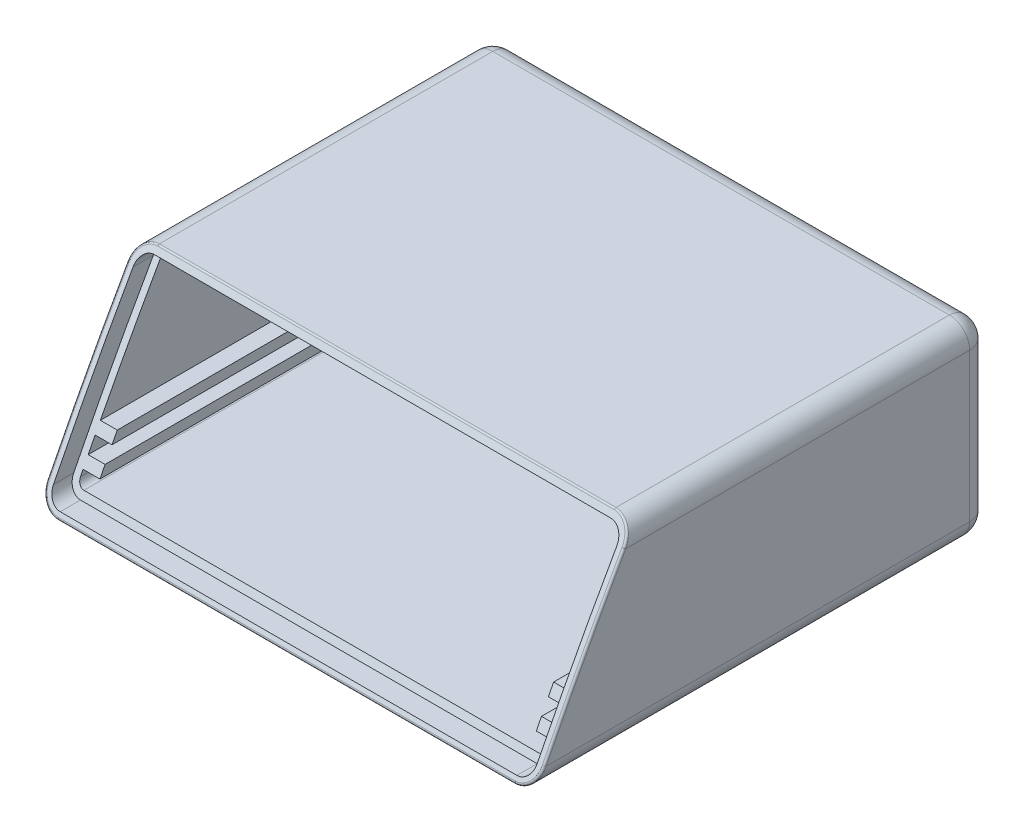
SolidWorks part; units mm, degrees
ref_plane "Front Plane" through (0, 0, 0) normal (0, 0, 1) x (1, 0, 0)
ref_plane "Top Plane" through (0, 0, 0) normal (0, 1, 0) x (1, 0, 0)
ref_plane "Right Plane" through (0, 0, 0) normal (1, 0, 0) x (0, 0, -1)
sketch "Sketch1" plane through (0, 0, 0) normal (0, 1, 0) x (1, 0, 0)
  line L1 (-36.79, -33.75) -> (36.79, -33.75)
  line L2 (-36.79, -33.75) -> (-36.79, 33.75)
  line L3 (-36.79, 33.75) -> (36.79, 33.75)
  line L4 (36.79, -33.75) -> (36.79, 33.75)
  line L5 (-36.79, -33.75) -> (36.79, 33.75) construction
  line L6 (-36.79, 33.75) -> (36.79, -33.75) construction
  point P0 (0, 0)
  dimension "D1" = 67.5
  dimension "D2" = 73.58
extrude "Boss-Extrude1" add sketch "Sketch1" along normal blind 28
fillet "Fillet1" radius 3 4 edges at (36.79, 28, 0) (36.79, 0, 0) (-36.79, 0, 0) (-36.79, 28, 0)
shell "Shell1" thickness 2
sketch "Sketch2" plane through (-36.79, 0, 0) normal (-1, 0, 0) x (0, 0, 1)
  line L0 (-33.75, 28) -> (33.75, 28) construction
  line L1 (18.75, 28) -> (33.75, 28)
  line L2 (33.75, 28) -> (33.75, 0)
  arc A0 (33.75, 0) -> (18.75, 28) centre (-392.2189, -210.1797) ccw
  dimension "D1" = 15
  dimension "D2" = 475
extrude "Cut-Extrude1" cut sketch "Sketch2" against normal through all
sketch "Sketch3" plane through (0, 0, -33.75) normal (0, 0, -1) x (-1, 0, 0)
  line L0 (-7.15, 18.7) -> (7.15, 18.7)
  line L1 (-6.95, 18.5) -> (6.95, 18.5) construction
  line L2 (-6.95, 18.5) -> (-6.95, 2.2) construction
  line L3 (-6.95, 2.2) -> (6.95, 2.2) construction
  line L4 (6.95, 18.5) -> (6.95, 2.2) construction
  line L5 (7.15, 18.7) -> (7.15, 2)
  line L6 (-7.15, 2) -> (7.15, 2)
  line L7 (-7.15, 18.7) -> (-7.15, 2)
  line L8 (27.25, 17.2) -> (38.3, 17.2)
  line L9 (27.45, 17) -> (38.1, 17) construction
  line L10 (27.45, 17) -> (27.45, 3.35) construction
  line L11 (27.45, 3.35) -> (38.1, 3.35) construction
  line L12 (38.1, 17) -> (38.1, 3.35) construction
  line L13 (38.3, 17.2) -> (38.3, 3.15)
  line L14 (27.25, 3.15) -> (38.3, 3.15)
  line L15 (27.25, 17.2) -> (27.25, 3.15)
  dimension "D1" = 0.2
  dimension "D2" = 0.2
fillet "Fillet2" radius 3 8 edges at (35.9113, 27.1213, -33.75) (36.79, 14, -33.75) (35.9113, 0.8787, -33.75) (0, 0, -33.75) (-35.9113, 0.8787, -33.75) (-36.79, 14, -33.75) (-35.9113, 27.1213, -33.75) (0, 28, -33.75)
sketch "Sketch4" plane through (0, 0, -31.75) normal (0, 0, 1) x (1, 0, 0)
  line L0 (33.79, 27) -> (-33.79, 27)
  line L1 (-35.79, 25) -> (-35.79, 3)
  line L2 (-33.79, 1) -> (33.79, 1)
  line L3 (35.79, 3) -> (35.79, 25)
  line L4 (33.79, 26) -> (-33.79, 26)
  line L5 (-34.79, 25) -> (-34.79, 3)
  line L6 (-33.79, 2) -> (33.79, 2)
  line L7 (34.79, 3) -> (34.79, 25)
  line L8 (33.79, 26) -> (-33.79, 26)
  line L9 (-34.79, 25) -> (-34.79, 3)
  line L10 (-33.79, 2) -> (33.79, 2)
  line L11 (34.79, 3) -> (34.79, 25)
  arc A0 (-33.79, 27) -> (-35.79, 25) centre (-33.79, 25) ccw
  arc A1 (-35.79, 3) -> (-33.79, 1) centre (-33.79, 3) ccw
  arc A2 (33.79, 1) -> (35.79, 3) centre (33.79, 3) ccw
  arc A3 (35.79, 25) -> (33.79, 27) centre (33.79, 25) ccw
  arc A4 (-33.79, 26) -> (-34.79, 25) centre (-33.79, 25) ccw
  arc A5 (-34.79, 3) -> (-33.79, 2) centre (-33.79, 3) ccw
  arc A6 (33.79, 2) -> (34.79, 3) centre (33.79, 3) ccw
  arc A7 (34.79, 25) -> (33.79, 26) centre (33.79, 25) ccw
  arc A8 (-33.79, 26) -> (-34.79, 25) centre (-33.79, 25) ccw
  arc A9 (-34.79, 3) -> (-33.79, 2) centre (-33.79, 3) ccw
  arc A10 (33.79, 2) -> (34.79, 3) centre (33.79, 3) ccw
  arc A11 (34.79, 25) -> (33.79, 26) centre (33.79, 25) ccw
  dimension "D1" = 0
  dimension "D2" = 1
extrude "Cut-Extrude3" cut sketch "Sketch4" against normal offset from surface (18.9934 mm away) 3 from offset 80
fillet "Fillet3" radius 0.3 8 edges at (35.773, 27.2511, 19.1831) (36.79, 14.0774, 26.5098) (35.5191, 0.5484, 33.479) (0, 0, 33.75) (-35.9799, 0.9496, 33.2802) (-36.79, 14.0774, 26.5098) (-35.4767, 27.4809, 19.0504) (0, 28, 18.75)
sketch "Sketch5" plane through (0, 0, -31.75) normal (0, 0, 1) x (1, 0, 0)
  line L1 (34.79, 5.25) -> (32.29, 5.25)
  line L2 (34.79, 5.25) -> (34.79, 3.75)
  line L3 (34.79, 3.75) -> (32.29, 3.75)
  line L4 (32.29, 5.25) -> (32.29, 3.75)
  line L5 (34.79, 7.05) -> (40.64, 7.05) construction
  line L6 (34.79, 7.25) -> (32.29, 7.25)
  line L7 (34.79, 7.25) -> (34.79, 8.75)
  line L8 (34.79, 8.75) -> (32.29, 8.75)
  line L9 (32.29, 7.25) -> (32.29, 8.75)
  line L10 (-40.64, 7.05) -> (40.64, 7.05) construction
  line L11 (40.64, 5.45) -> (34.79, 5.45) construction
  line L12 (-40.64, 5.45) -> (40.64, 5.45) construction
  line L14 (-34.79, 8.75) -> (-32.29, 8.75)
  line L15 (-34.79, 8.75) -> (-34.79, 7.25)
  line L16 (-34.79, 7.25) -> (-32.29, 7.25)
  line L17 (-32.29, 8.75) -> (-32.29, 7.25)
  line L18 (-34.79, 25) -> (-34.79, 3) construction
  line L19 (-34.79, 5.25) -> (-32.29, 5.25)
  line L20 (-34.79, 5.25) -> (-34.79, 3.75)
  line L21 (-34.79, 3.75) -> (-32.29, 3.75)
  line L22 (-32.29, 5.25) -> (-32.29, 3.75)
  line L23 (34.79, 25) -> (34.79, 3) construction
  dimension "D1" = 0.2
  dimension "D2" = 0.2
  dimension "D3" = 1.5
  dimension "D4" = 2.5
extrude "Boss-Extrude2" add sketch "Sketch5" along normal up to surface (59.8691 mm away)
sketch "Sketch6" plane through (0, 0, -33.75) normal (0, 0, -1) x (-1, 0, 0)
  line L0 (-7.15, 18.7) -> (7.15, 18.7)
  line L1 (-6.95, 18.5) -> (6.95, 18.5) construction
  line L2 (-6.95, 18.5) -> (-6.95, 2.2) construction
  line L3 (-6.95, 2.2) -> (6.95, 2.2) construction
  line L4 (6.95, 18.5) -> (6.95, 2.2) construction
  line L5 (7.15, 18.7) -> (7.15, 2)
  line L6 (-7.15, 2) -> (7.15, 2)
  line L7 (-7.15, 18.7) -> (-7.15, 2)
  line L8 (20.9, 17.2) -> (31.95, 17.2)
  line L9 (21.1, 17) -> (31.75, 17) construction
  line L10 (21.1, 17) -> (21.1, 3.35) construction
  line L11 (21.1, 3.35) -> (31.75, 3.35) construction
  line L12 (31.75, 17) -> (31.75, 3.35) construction
  line L13 (31.95, 17.2) -> (31.95, 3.15)
  line L14 (20.9, 3.15) -> (31.95, 3.15)
  line L15 (20.9, 17.2) -> (20.9, 3.15)
  dimension "D1" = 0.2
  dimension "D2" = 0.2
extrude "Cut-Extrude4" cut sketch "Sketch6" against normal up to surface (2 mm away) up to face at (0, 8.8333, -31.75)
